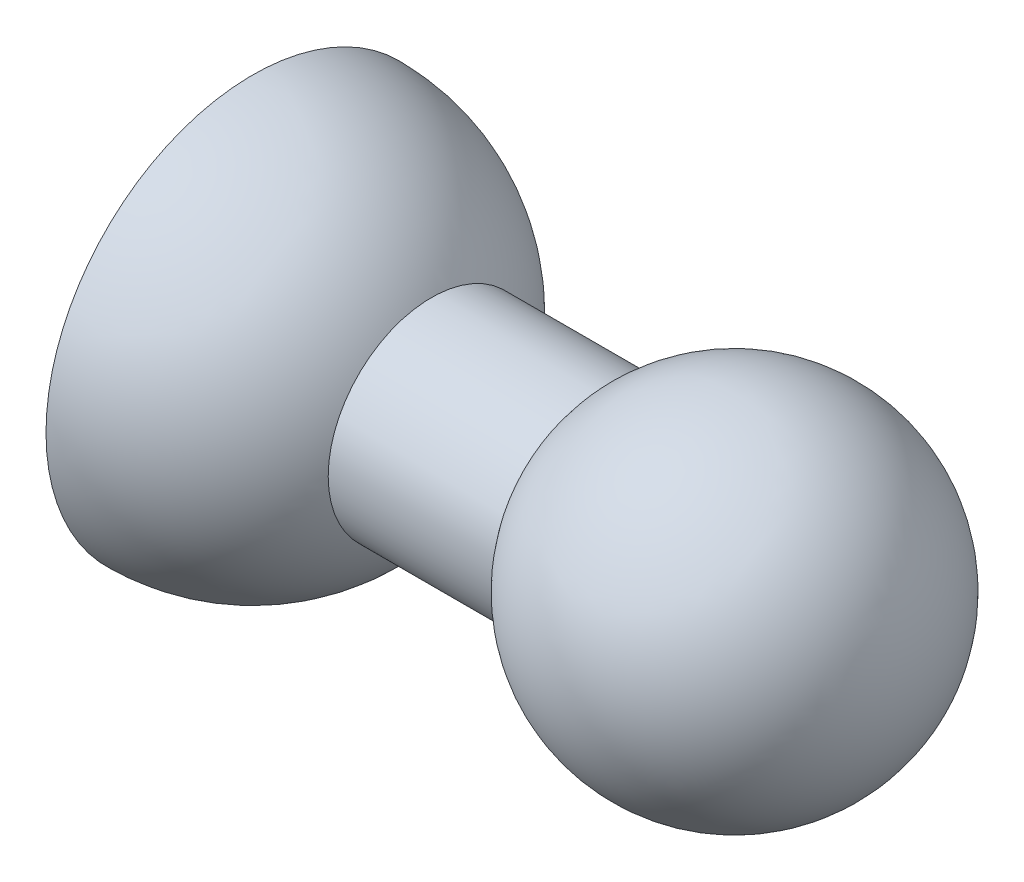
SolidWorks part; units mm, degrees
ref_plane "Alzado" through (0, 0, 0) normal (0, 0, 1) x (1, 0, 0)
ref_plane "Planta" through (0, 0, 0) normal (0, 1, 0) x (1, 0, 0)
ref_plane "Vista lateral" through (0, 0, 0) normal (1, 0, 0) x (0, 0, -1)
sketch "Croquis1" plane through (0, 0, 0) normal (0, 1, 0) x (1, 0, 0)
  line L2 (0, 0) -> (25, 0) construction
  arc A0 (25, 0) -> (0, 25) centre (0, 0) ccw
  dimension "D1" = 50
revolve "Revolución-Lámina1" add sketch "Croquis1" angle 360 about L2
sketch "Croquis2" plane through (0, 0, 0) normal (-1, 0, 0) x (0, 0, 1)
  circle A0 centre (0, 0) radius 15
  dimension "D1" = 30
extrude "Saliente-Extruir2" add sketch "Croquis2" against normal blind 10 and the other way up to surface from offset 40 offset against normal yes
sketch "Croquis3" plane through (0, 0, 0) normal (0, 0, 1) x (1, 0, 0)
  line L1 (50, -15) -> (50, 15) construction
  line L2 (50, 0) -> (50, 15)
  line L3 (50, 0) -> (95, 0) construction
  line L4 (50, 0) -> (95, 0)
  arc A0 (95, 0) -> (50, 15) centre (70, 0) ccw
  dimension "D1" = 20
revolve "Revolución1" add sketch "Croquis3" angle 360 about L3
